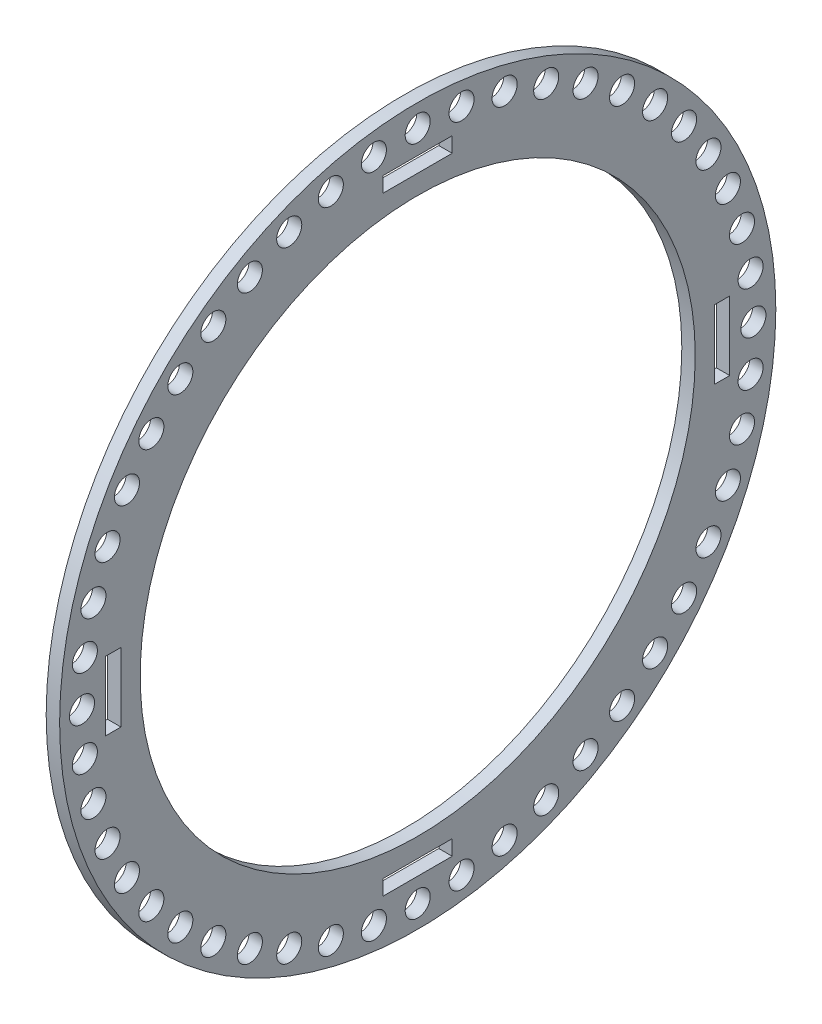
SolidWorks part; units mm, degrees
material "AISI 304"
ref_plane "Front Plane" through (0, 0, 0) normal (0, 0, 1) x (1, 0, 0)
ref_plane "Top Plane" through (0, 0, 0) normal (0, 1, 0) x (1, 0, 0)
ref_plane "Right Plane" through (0, 0, 0) normal (1, 0, 0) x (0, 0, -1)
sketch "Sketch1" plane through (0, 0, 0) normal (1, 0, 0) x (0, 0, -1)
  line L0 (0, 0) -> (0, 40) construction
  line L62 (-3.85, 34.85) -> (3.85, 34.85)
  line L63 (-3.85, 34.85) -> (-3.85, 33.15)
  line L64 (-3.85, 33.15) -> (3.85, 33.15)
  line L65 (3.85, 34.85) -> (3.85, 33.15)
  line L66 (-3.85, 34.85) -> (3.85, 33.15) construction
  line L67 (-3.85, 33.15) -> (3.85, 34.85) construction
  line L103 (34.85, 3.85) -> (34.85, -3.85)
  line L104 (33.15, 3.85) -> (33.15, -3.85)
  line L105 (34.85, 3.85) -> (33.15, 3.85)
  line L106 (34.85, -3.85) -> (33.15, -3.85)
  line L107 (3.85, -34.85) -> (-3.85, -34.85)
  line L108 (3.85, -33.15) -> (-3.85, -33.15)
  line L109 (3.85, -34.85) -> (3.85, -33.15)
  line L110 (-3.85, -34.85) -> (-3.85, -33.15)
  line L111 (-34.85, -3.85) -> (-34.85, 3.85)
  line L112 (-33.15, -3.85) -> (-33.15, 3.85)
  line L113 (-34.85, -3.85) -> (-33.15, -3.85)
  line L114 (-34.85, 3.85) -> (-33.15, 3.85)
  circle A3 centre (0, 0) radius 40
  circle A25 centre (0, 0) radius 31
  point P9 (0, -20)
  point P11 (-20, 0)
  point P22 (0, 34)
  point P29 (20, 0)
  point P31 (0, 30)
  point P75 (0, 0)
  point P81 (0, -1)
  point P93 (0, 0)
  point P95 (0, 0)
  dimension "D2" = 80
  dimension "D3" = 62
  dimension "D7" = 7.7
  dimension "D8" = 1.7
  dimension "D9" = 10
  dimension "D12" = 6
  dimension "D14" = 4
extrude "Boss-Extrude4" add sketch "Sketch1" along normal blind 1.5
sketch "Sketch2" plane through (1.5, 0, 0) normal (1, 0, 0) x (0, 0, -1)
  circle A0 centre (0, 37.5) radius 1.4
  circle A1 centre (0, 0) radius 40 construction
  dimension "D2" = 2.8
  dimension "D1" = 37.5
extrude "Cut-Extrude2" cut sketch "Sketch2" against normal blind 1.5
pattern_circular "CirPattern3" count 48 over 360 about axis through (0, 0, 0) along (1, 0, 0) of "Cut-Extrude2"
